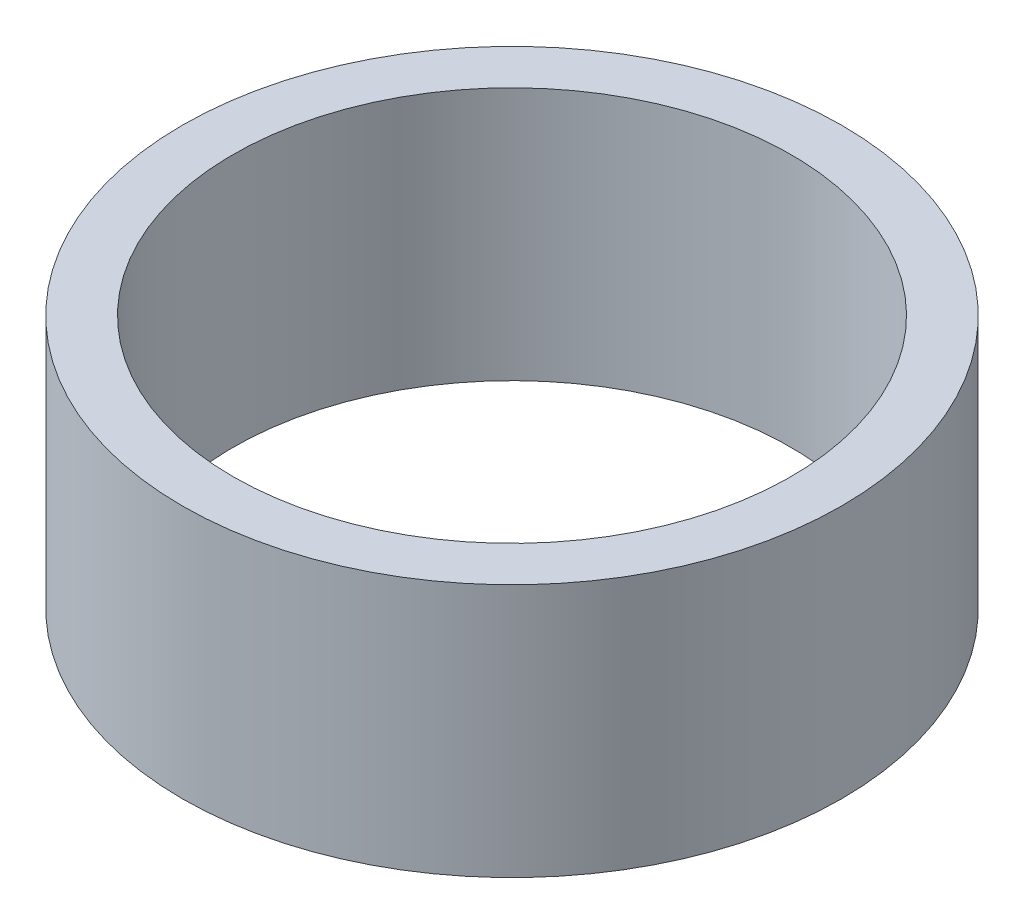
SolidWorks part; units mm, degrees
ref_plane "Front Plane" through (0, 0, 0) normal (0, 0, 1) x (1, 0, 0)
ref_plane "Top Plane" through (0, 0, 0) normal (0, 1, 0) x (1, 0, 0)
ref_plane "Right Plane" through (0, 0, 0) normal (1, 0, 0) x (0, 0, -1)
sketch "Sketch1" plane through (0, 0, 0) normal (0, 1, 0) x (1, 0, 0)
  circle A0 centre (0, 0) radius 11
  circle A1 centre (0, 0) radius 13
  dimension "D1" = 22
  dimension "D2" = 2
extrude "Boss-Extrude1" add sketch "Sketch1" along normal blind 10
